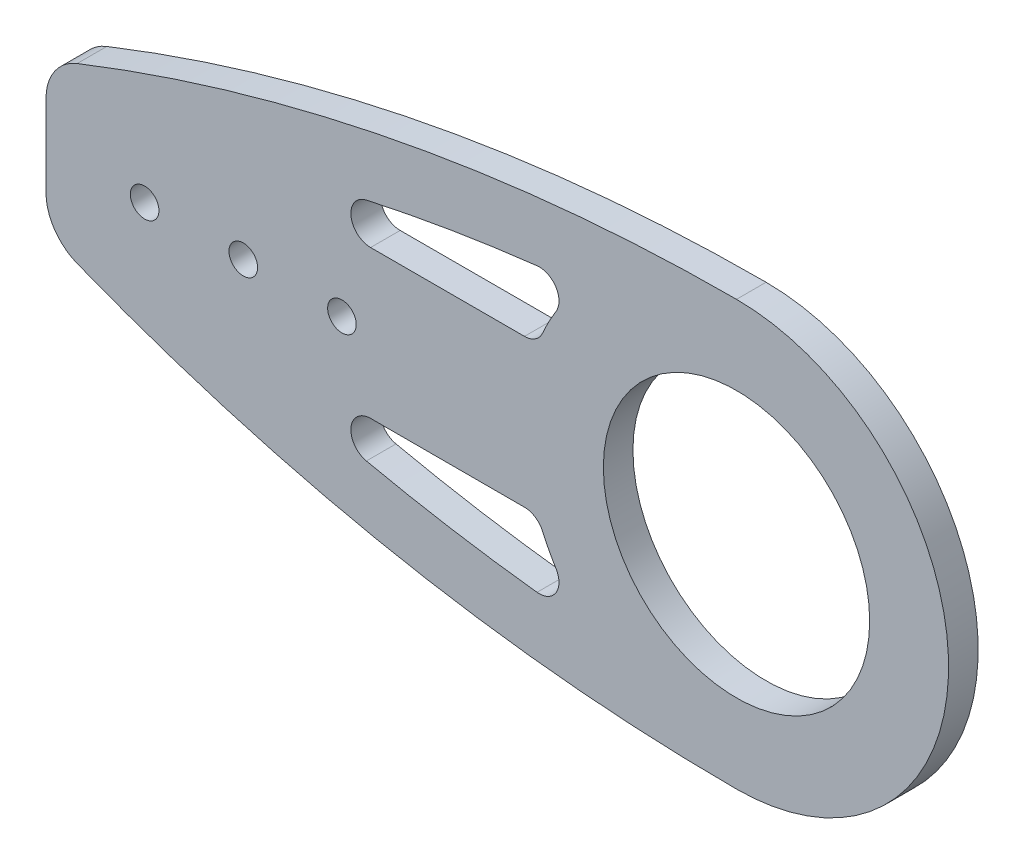
SolidWorks part; units mm, degrees
material "Thornel Mat VMA"
ref_plane "前视基准面" through (0, 0, 0) normal (0, 0, 1) x (1, 0, 0)
ref_plane "上视基准面" through (0, 0, 0) normal (0, 1, 0) x (1, 0, 0)
ref_plane "右视基准面" through (0, 0, 0) normal (1, 0, 0) x (0, 0, -1)
other "Configuration Table"
sketch "草图1" plane through (0, 0, 0) normal (0, 0, 1) x (1, 0, 0)
  line L0 (0, -7.5) -> (20.1494, -7.5) construction
  line L1 (0, 0) -> (-48.5259, 0) construction
  line L2 (0, 0) -> (0, -15) construction
  line L3 (0, -15) -> (-48.5259, -15) construction
  line L4 (-48.5259, 0) -> (-48.5259, -15) construction
  line L5 (0, 0) -> (-49.8506, 0) construction
  line L6 (-49.8506, 0) -> (-49.8506, -15) construction
  line L7 (-49.8506, -15) -> (0, -15) construction
  line L8 (5.1494, 0) -> (5.1494, -15) construction
  line L9 (-49.8506, 0) -> (-49.8506, -15)
  circle A0 centre (20.1494, -7.5) radius 13.5
  arc A1 (0, -15) -> (0, 0) centre (20.1494, -7.5) ccw construction
  arc A2 (-49.8506, 0) -> (20.1494, 14) centre (20.1494, -168) cw
  arc A3 (-49.8506, -15) -> (20.1494, -29) centre (20.1494, 153) ccw
  arc A4 (20.1494, 14) -> (20.1494, -29) centre (20.1494, -7.5) cw
  dimension "D2" = 27
  dimension "D3" = 8
  dimension "D1" = 15
  dimension "D4" = 55
  dimension "D5" = 15
extrude "凸台-拉伸1" add sketch "草图1" along normal blind 3
sketch "草图2" plane through (0, 0, 3) normal (0, 0, 1) x (1, 0, 0)
  line L0 (-49.8506, -7.5) -> (6.6494, -7.5) construction
  line L2 (-49.8506, 0) -> (-49.8506, -15) construction
  line L3 (-39.8506, -7.5) -> (-29.8506, -7.5) construction
  circle A1 centre (-39.8506, -7.5) radius 1.45
  circle A4 centre (-29.8506, -7.5) radius 1.45
  circle A5 centre (-19.8506, -7.5) radius 1.45
  circle A6 centre (20.1494, -7.5) radius 13.5 construction
  dimension "D1" = 2.9
  dimension "D2" = 10
  dimension "D4" = 10
  dimension "D3" = 3
extrude "切除-拉伸1" cut sketch "草图2" against normal through all
fillet "圆角1" radius 5 2 edges at (-49.8506, -15, 1.5) (-49.8506, 0, 1.5)
sketch "草图3" plane through (0, 0, 3) normal (0, 0, 1) x (1, 0, 0)
  line L0 (-32.3101, 0) -> (0, 0)
  line L1 (-38.5325, 0) -> (0, 0) construction
  line L2 (-38.5325, 0) -> (-38.5325, -15) construction
  line L3 (-38.5325, -15) -> (0, -15) construction
  line L4 (0, 0) -> (0, -15) construction
  line L5 (-32.3101, -15) -> (0, -15)
  circle A0 centre (20.1494, -7.5) radius 21.5 construction
  arc A1 (20.1494, -29) -> (20.1494, 14) centre (20.1494, -7.5) ccw construction
  arc A13 (20.1494, 8) -> (-44.4833, -4.2972) centre (20.1494, -168) ccw
  arc A14 (4.5622, 7.3084) -> (-32.3101, 0) centre (20.1494, -168) ccw
  arc A15 (4.5622, 7.3084) -> (0, 0) centre (20.1494, -7.5) ccw
  arc A16 (-44.4833, -10.7028) -> (20.1494, -23) centre (20.1494, 153) ccw
  arc A17 (-32.3101, -15) -> (4.5622, -22.3084) centre (20.1494, 153) ccw
  arc A18 (4.5622, -22.3084) -> (0, -15) centre (20.1494, -7.5) cw
  point P7 (-38.5325, -7.5)
  dimension "D1" = 15
  dimension "D2" = 6
  dimension "D3" = 6
extrude "切除-拉伸2" cut sketch "草图3" against normal through all
fillet "圆角2" radius 2 6 edges at (0, 0, 1.5) (-32.3101, -15, 1.5) (0, -15, 1.5) (4.5622, -22.3084, 1.5) (4.5622, 7.3084, 1.5) (-32.3101, 0, 1.5)
